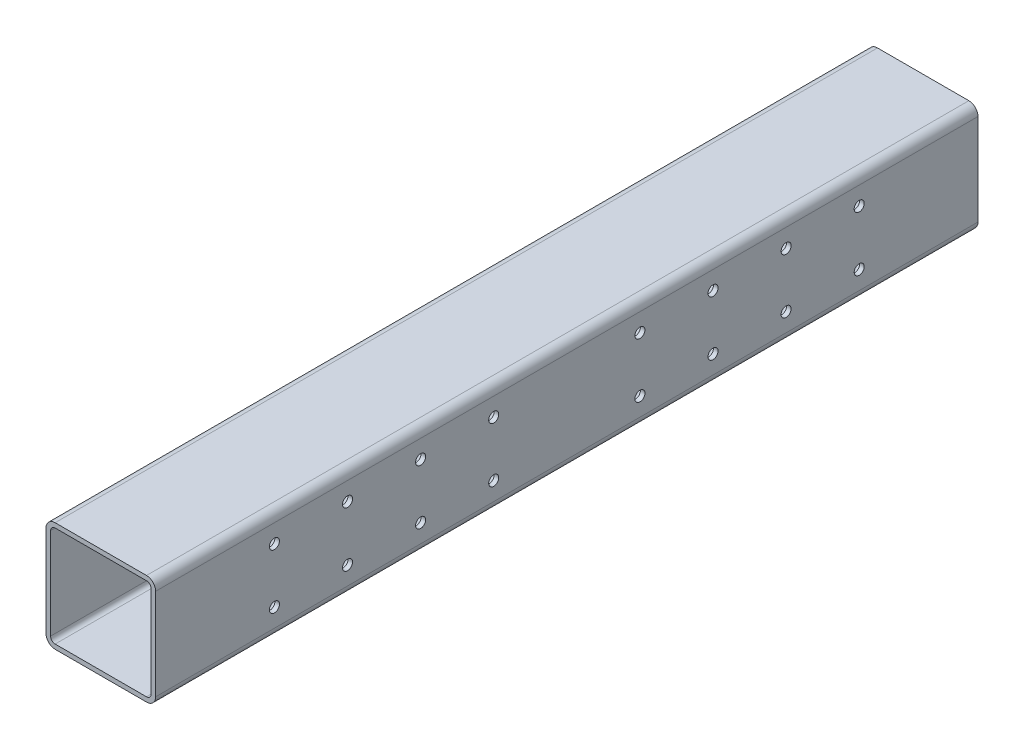
SolidWorks part; units mm, degrees
material "ASTM A36 Steel"
ref_plane "Front Plane" through (0, 0, 0) normal (0, 0, 1) x (1, 0, 0)
ref_plane "Top Plane" through (0, 0, 0) normal (0, 1, 0) x (1, 0, 0)
ref_plane "Right Plane" through (0, 0, 0) normal (1, 0, 0) x (0, 0, -1)
sketch "Sketch1" plane through (0, 0, 0) normal (0, 0, 1) x (1, 0, 0)
  line L0 (-63.5, 69.85) -> (63.5, 69.85)
  line L1 (-63.5, -76.2) -> (63.5, -76.2)
  line L2 (-76.2, -63.5) -> (-76.2, 63.5)
  line L3 (-63.5, 76.2) -> (63.5, 76.2)
  line L4 (76.2, -63.5) -> (76.2, 63.5)
  line L5 (-76.2, -76.2) -> (76.2, 76.2) construction
  line L6 (-76.2, 76.2) -> (76.2, -76.2) construction
  line L7 (69.85, -63.5) -> (69.85, 63.5)
  line L8 (-63.5, -69.85) -> (63.5, -69.85)
  line L9 (-69.85, -63.5) -> (-69.85, 63.5)
  arc A0 (63.5, -76.2) -> (76.2, -63.5) centre (63.5, -63.5) ccw
  arc A1 (-76.2, 63.5) -> (-63.5, 76.2) centre (-63.5, 63.5) cw
  arc A2 (-63.5, -76.2) -> (-76.2, -63.5) centre (-63.5, -63.5) cw
  arc A3 (63.5, 76.2) -> (76.2, 63.5) centre (63.5, 63.5) cw
  arc A4 (63.5, 69.85) -> (69.85, 63.5) centre (63.5, 63.5) cw
  arc A5 (63.5, -69.85) -> (69.85, -63.5) centre (63.5, -63.5) ccw
  arc A6 (-63.5, -69.85) -> (-69.85, -63.5) centre (-63.5, -63.5) cw
  arc A7 (-69.85, 63.5) -> (-63.5, 69.85) centre (-63.5, 63.5) cw
  point P0 (0, 0)
  dimension "D3" = 12.7
  dimension "D1" = 152.4
  dimension "D2" = 152.4
  dimension "D4" = 6.35
extrude "Boss-Extrude1" add sketch "Sketch1" along normal mid plane 1143
sketch "Sketch2" plane through (-76.2, 0, 0) normal (-1, 0, 0) x (0, 0, 1)
  line L0 (571.5, 76.2) -> (-571.5, 76.2) construction
  line L1 (83.82, 0) -> (-83.82, 0) construction
  line L2 (0, -83.82) -> (0, 83.82) construction
  circle A0 centre (-101.6, 38.1) radius 6.985
  circle A1 centre (-203.2, 38.1) radius 6.985
  circle A2 centre (-304.8, 38.1) radius 6.985
  circle A3 centre (-304.8, -38.1) radius 6.985
  circle A4 centre (-203.2, -38.1) radius 6.985
  circle A5 centre (-101.6, -38.1) radius 6.985
  circle A6 centre (101.6, -38.1) radius 6.985
  circle A7 centre (203.2, -38.1) radius 6.985
  circle A8 centre (304.8, -38.1) radius 6.985
  circle A9 centre (304.8, 38.1) radius 6.985
  circle A10 centre (203.2, 38.1) radius 6.985
  circle A11 centre (101.6, 38.1) radius 6.985
  circle A12 centre (-406.4, 38.1) radius 6.985
  circle A13 centre (-406.4, -38.1) radius 6.985
  circle A14 centre (406.4, -38.1) radius 6.985
  circle A15 centre (406.4, 38.1) radius 6.985
  point P6 (0, 0)
  dimension "D1" = 13.97
  dimension "D6" = 101.6
  dimension "D2" = 101.6
  dimension "D3" = 101.6
  dimension "D4" = 101.6
  dimension "D5" = 38.1
extrude "Cut-Extrude1" cut sketch "Sketch2" against normal through all
equation "\"PRIMER_USAGE\"= ( \"SW-SurfaceArea\" / 144 ) / 135"
equation "\"WET_PAINT_USAGE\"= ( \"SW-SurfaceArea\" / 144 ) / 125"
equation "\"POWDERCOAT_USAGE\"= ( \"SW-SurfaceArea\" / 144 ) / 29.79"
equation "\"DECKOVER_USAGE\"= ( \"SW-SurfaceArea\" / 144 ) / 75"
equation "\"SW_NON-SKID\"= ( \"SW-SurfaceArea\" / 144 ) / 165"
equation "\"TYPE_1_ANODIZATING\"= ( \"SW-SurfaceArea\" * 0.0001 )"
equation "\"TYPE_2_ANODIZING\"= ( \"SW-SurfaceArea\" * 0.0005 )"
equation "\"TYPE_3_ANODIZING-HARDCOAT\"= ( \"SW-SurfaceArea\" * 0.003 )"
